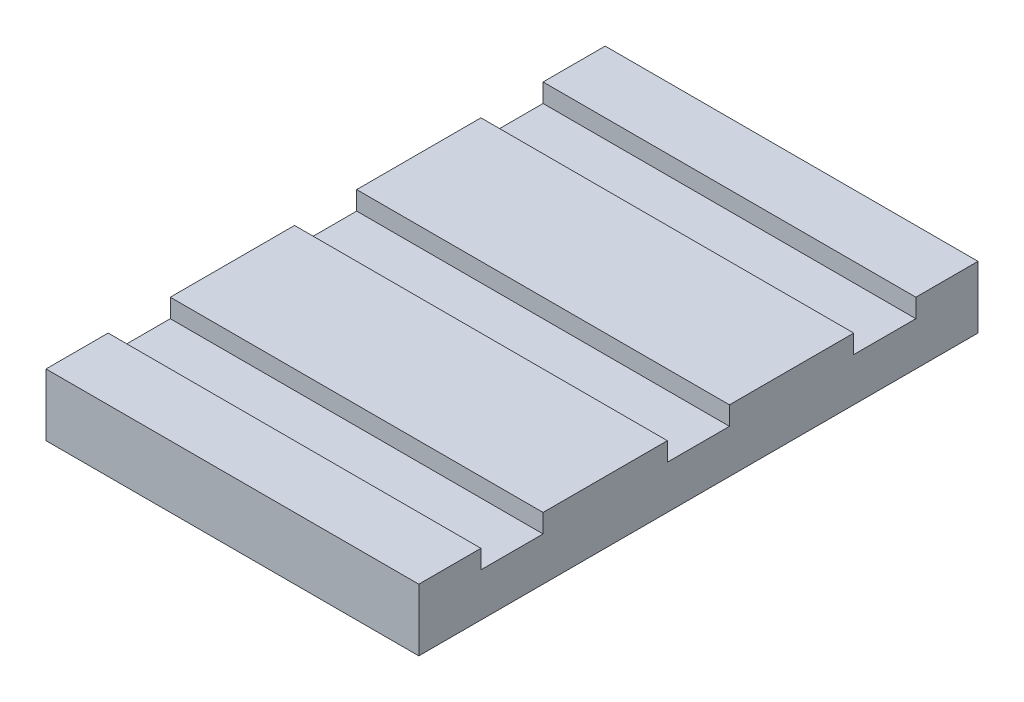
SolidWorks part; units mm, degrees
material "Acrylic (Medium-high impact)"
ref_plane "Front Plane" through (0, 0, 0) normal (0, 0, 1) x (1, 0, 0)
ref_plane "Top Plane" through (0, 0, 0) normal (0, 1, 0) x (1, 0, 0)
ref_plane "Right Plane" through (0, 0, 0) normal (1, 0, 0) x (0, 0, -1)
sketch "Sketch2" plane through (0, 0, 0) normal (0, 1, 0) x (1, 0, 0)
  line L1 (-38.1, 57.15) -> (38.1, 57.15)
  line L2 (-38.1, 57.15) -> (-38.1, -57.15)
  line L3 (-38.1, -57.15) -> (38.1, -57.15)
  line L4 (38.1, 57.15) -> (38.1, -57.15)
  line L5 (-38.1, 57.15) -> (38.1, -57.15) construction
  line L6 (-38.1, -57.15) -> (38.1, 57.15) construction
  point P0 (0, 0)
  dimension "D1" = 76.2
  dimension "D2" = 114.3
extrude "Boss-Extrude1" add sketch "Sketch2" along normal blind 12.7
sketch "Sketch4" plane through (38.1, 0, 0) normal (1, 0, 0) x (0, 0, -1)
  line L0 (-57.15, 12.7) -> (57.15, 12.7) construction
  line L1 (-44.45, 12.7) -> (-31.75, 12.7)
  line L2 (-44.45, 12.7) -> (-44.45, 8.89)
  line L3 (-44.45, 8.89) -> (-31.75, 8.89)
  line L4 (-31.75, 12.7) -> (-31.75, 8.89)
  line L5 (-57.15, 12.7) -> (-57.15, 0) construction
  dimension "D1" = 3.81
  dimension "D2" = 12.7
  dimension "D3" = 12.7
extrude "Cut-Extrude1" cut sketch "Sketch4" against normal blind 76.2
mirror "Mirror1" about plane through (0, 0, 0) normal (0, 0, 1) of "Cut-Extrude1"
sketch "Sketch5" plane through (38.1, 0, 0) normal (1, 0, 0) x (0, 0, -1)
  line L0 (-31.75, 12.7) -> (31.75, 12.7) construction
  line L1 (-6.35, 12.7) -> (6.35, 12.7)
  line L2 (-6.35, 12.7) -> (-6.35, 8.89)
  line L3 (-6.35, 8.89) -> (6.35, 8.89)
  line L4 (6.35, 12.7) -> (6.35, 8.89)
  point P6 (0, 8.89)
  dimension "D1" = 3.81
  dimension "D2" = 12.7
extrude "Cut-Extrude2" cut sketch "Sketch5" against normal blind 76.2
mirror "Mirror3" [suppressed] about plane through (0, 0, 0) normal (1, 0, 0)
